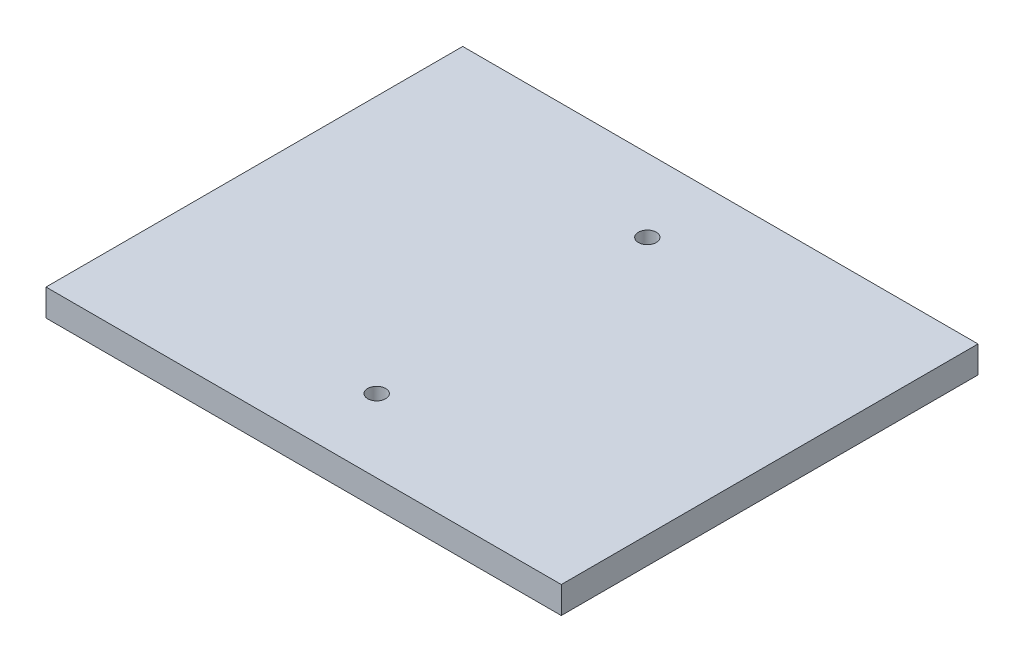
SolidWorks part; units mm, degrees
ref_plane "前视基准面" through (0, 0, 0) normal (0, 0, 1) x (1, 0, 0)
ref_plane "上视基准面" through (0, 0, 0) normal (0, 1, 0) x (1, 0, 0)
ref_plane "右视基准面" through (0, 0, 0) normal (1, 0, 0) x (0, 0, -1)
other "Configuration Table"
sketch "草图1" plane through (0, 0, 0) normal (0, 1, 0) x (1, 0, 0)
  line L1 (-28.75, -23.25) -> (28.75, -23.25)
  line L2 (-28.75, -23.25) -> (-28.75, 23.25)
  line L3 (-28.75, 23.25) -> (28.75, 23.25)
  line L4 (28.75, -23.25) -> (28.75, 23.25)
  line L5 (-28.75, -23.25) -> (28.75, 23.25) construction
  line L6 (-28.75, 23.25) -> (28.75, -23.25) construction
  point P0 (0, 0)
  dimension "D1" = 57.5
  dimension "D5" = 46.5
extrude "凸台-拉伸1" add sketch "草图1" along normal blind 3
sketch "草图2" plane through (0, 3, 0) normal (0, 1, 0) x (1, 0, 0)
  line L0 (-28.75, -23.25) -> (28.75, -23.25) construction
  line L1 (0, -15.1) -> (0, 15.1) construction
  circle A0 centre (0, -15.1) radius 1
  circle A1 centre (0, 15.1) radius 1
  dimension "D1" = 2
  dimension "D2" = 8.15
extrude "切除-拉伸1" cut sketch "草图2" against normal through all
sketch "草图4" plane through (0, 0, 0) normal (0, -1, 0) x (1, 0, 0)
  line L0 (-37.8655, 0) -> (36.4283, 0) construction
  line L1 (0, 24.9937) -> (0, -26.2434) construction
  line L2 (-28.75, 23.25) -> (28.75, 23.25) construction
  line L3 (-28.75, 23.25) -> (-28.75, -23.25) construction
  circle A0 centre (-20.75, 15.25) radius 2.6
  circle A2 centre (20.75, 15.25) radius 2.6
  circle A3 centre (-20.75, -15.25) radius 2.6
  circle A4 centre (20.75, -15.25) radius 2.6
  point P7 (36.4283, 0)
  dimension "D1" = 5.2
  dimension "D2" = 8
  dimension "D3" = 8
extrude "切除-拉伸2" cut sketch "草图4" against normal blind 0.8
